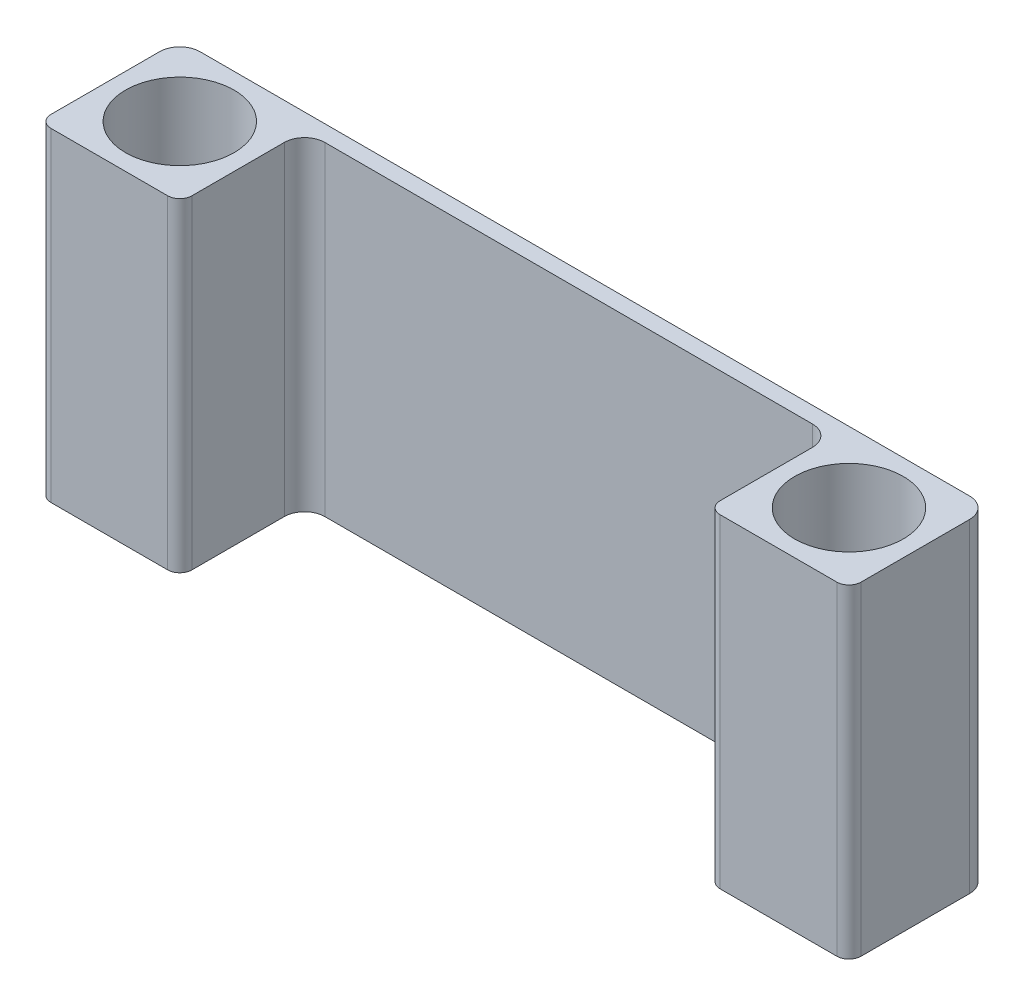
SolidWorks part; units mm, degrees
ref_plane "Front Plane" through (0, 0, 0) normal (0, 0, 1) x (1, 0, 0)
ref_plane "Top Plane" through (0, 0, 0) normal (0, 1, 0) x (1, 0, 0)
ref_plane "Right Plane" through (0, 0, 0) normal (1, 0, 0) x (0, 0, -1)
sketch "Sketch1" plane through (0, 0, 0) normal (0, 1, 0) x (1, 0, 0)
  line L1 (-17.4, 17.4) -> (17.4, 17.4)
  line L2 (-17.4, 17.4) -> (-17.4, -17.4)
  line L3 (-17.4, -17.4) -> (17.4, -17.4)
  line L4 (17.4, 13.4) -> (17.4, -17.4)
  line L5 (-17.4, 17.4) -> (17.4, -17.4) construction
  line L6 (-17.4, -17.4) -> (17.4, 17.4) construction
  line L11 (17.4, 17.4) -> (82.6, 17.4)
  line L13 (17.4, 13.4) -> (82.6, 13.4)
  line L14 (82.6, 17.4) -> (82.6, 13.4)
  circle A0 centre (0, 0) radius 13.4
  dimension "D1" = 26.8
  dimension "D2" = 34.8
  dimension "D3" = 34.8
extrude "Boss-Extrude1" add sketch "Sketch1" along normal blind 80 contours L14 L11 L4 L13 | L4 L1 L2 L3 A0
mirror "Mirror3" about plane through (82.6, 80, 0) normal (1, 0, 0) of "Boss-Extrude1"
fillet "Fillet1" radius 5 4 edges at (17.4, 40, -13.4) (147.8, 40, -13.4) (182.6, 40, -17.4) (-17.4, 40, -17.4)
fillet "Fillet2" radius 3 4 edges at (182.6, 40, 17.4) (147.8, 40, 17.4) (17.4, 40, 17.4) (-17.4, 40, 17.4)
